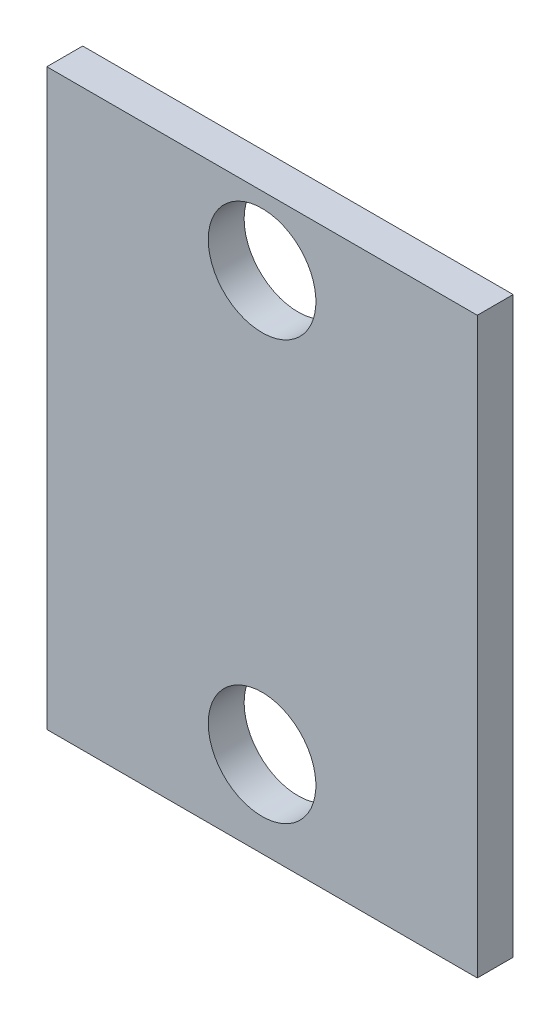
SolidWorks part; units mm, degrees
ref_plane "Front" through (0, 0, 0) normal (0, 0, 1) x (1, 0, 0)
ref_plane "Top" through (0, 0, 0) normal (0, 1, 0) x (1, 0, 0)
ref_plane "Right" through (0, 0, 0) normal (1, 0, 0) x (0, 0, -1)
sketch "Sketch1" plane through (0, 0, 0) normal (0, 0, 1) x (1, 0, 0)
  line L0 (0, -8.89) -> (19.05, -8.89) construction
  line L1 (0, 0) -> (19.05, 0)
  line L2 (0, 0) -> (0, -25.4)
  line L3 (0, -25.4) -> (19.05, -25.4)
  line L4 (19.05, 0) -> (19.05, -25.4)
  point P7 (9.525, -21.59)
  point P8 (9.525, -3.048)
  point P9 (0.375, -0.1268)
  dimension "D1" = 19.05
  dimension "D2" = 25.4
  dimension "D3" = 16.51
  dimension "D4" = 12.7
  dimension "D5" = 5.842
  dimension "D6" = 9.525
  dimension "D7" = 9.525
extrude "Boss-Extrude1" add sketch "Sketch1" along normal blind 1.5875
hole_wizard "3/16 (0.1875) Diameter Hole1" positions "Sketch4" profile "Sketch3" hole size "3/16" standard "ANSI Inch" end condition through all
sketch "Sketch4" plane through (0, 0, 0) normal (0, 0, -1) x (-1, 0, 0)
  point P0 (-9.525, -3.048)
  point P3 (-9.525, -21.59)
sketch "Sketch3" plane through (9.525, -3.048, 0) normal (1, 0, 0) x (0, 1, 0)
  line L0 (0, 0) -> (0, 1.5875)
  line L1 (0, 1.5875) -> (2.3812, 1.5875)
  line L2 (2.3812, 1.5875) -> (2.3812, 0)
  line L5 (2.3812, 0) -> (0, 0)
  line L11 (0, -6.35) -> (0, 107.95) construction
  dimension "Thru Hole Dia." = 4.7625
  dimension "Thru Hole Depth" = 1.5875
